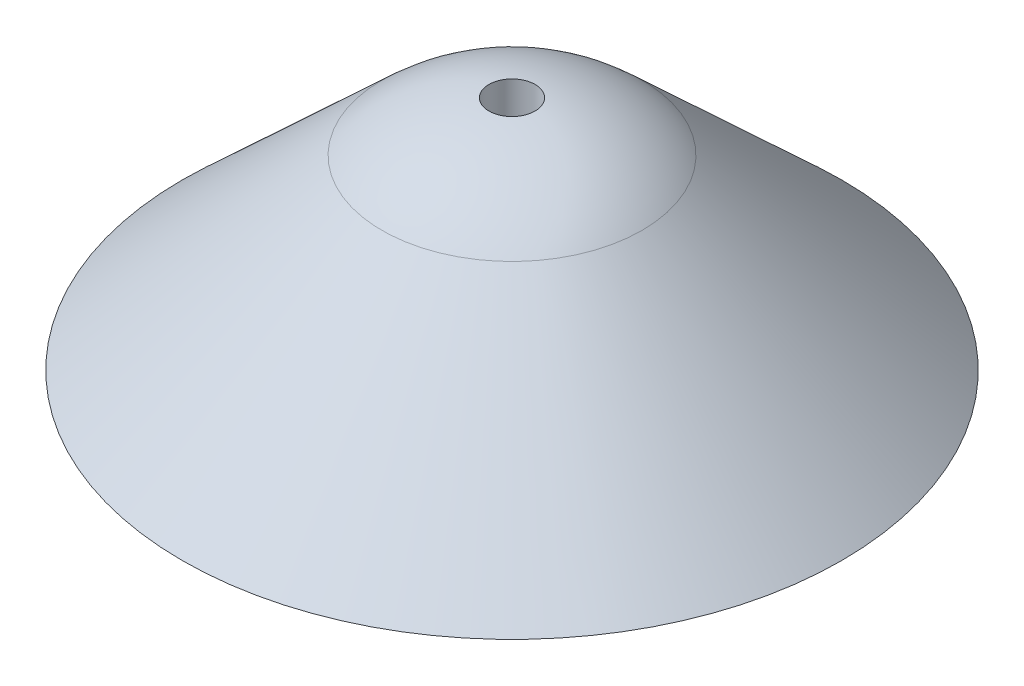
SolidWorks part; units mm, degrees
ref_plane "Front Plane" through (0, 0, 0) normal (0, 0, 1) x (1, 0, 0)
ref_plane "Top Plane" through (0, 0, 0) normal (0, 1, 0) x (1, 0, 0)
ref_plane "Right Plane" through (0, 0, 0) normal (1, 0, 0) x (0, 0, -1)
sketch "Sketch1" plane through (0, 0, 0) normal (0, 0, 1) x (1, 0, 0)
  line L0 (0, 0) -> (25, 0)
  line L1 (0, 0) -> (0, 18)
  line L2 (0, 18) -> (-15.7367, 18) construction
  line L3 (9.8642, 14.1144) -> (25, 0)
  arc A0 (0, 18) -> (9.8642, 14.1144) centre (0, 3.5364) cw
  point P6 (0, 24.2632)
  point P8 (0, 21.0829)
  point P9 (0, 23.3859)
  point P10 (0, 25.9082)
  dimension "D1" = 43
  dimension "D2" = 25
  dimension "D3" = 18
revolve "Revolve1" add sketch "Sketch1" angle 360 about L1
sketch "Sketch2" plane through (0, 0, 0) normal (0, -1, 0) x (1, 0, 0)
  circle A0 centre (0, 0) radius 1.75
  dimension "D1" = 3.5
extrude "Cut-Extrude1" cut sketch "Sketch2" against normal through all
